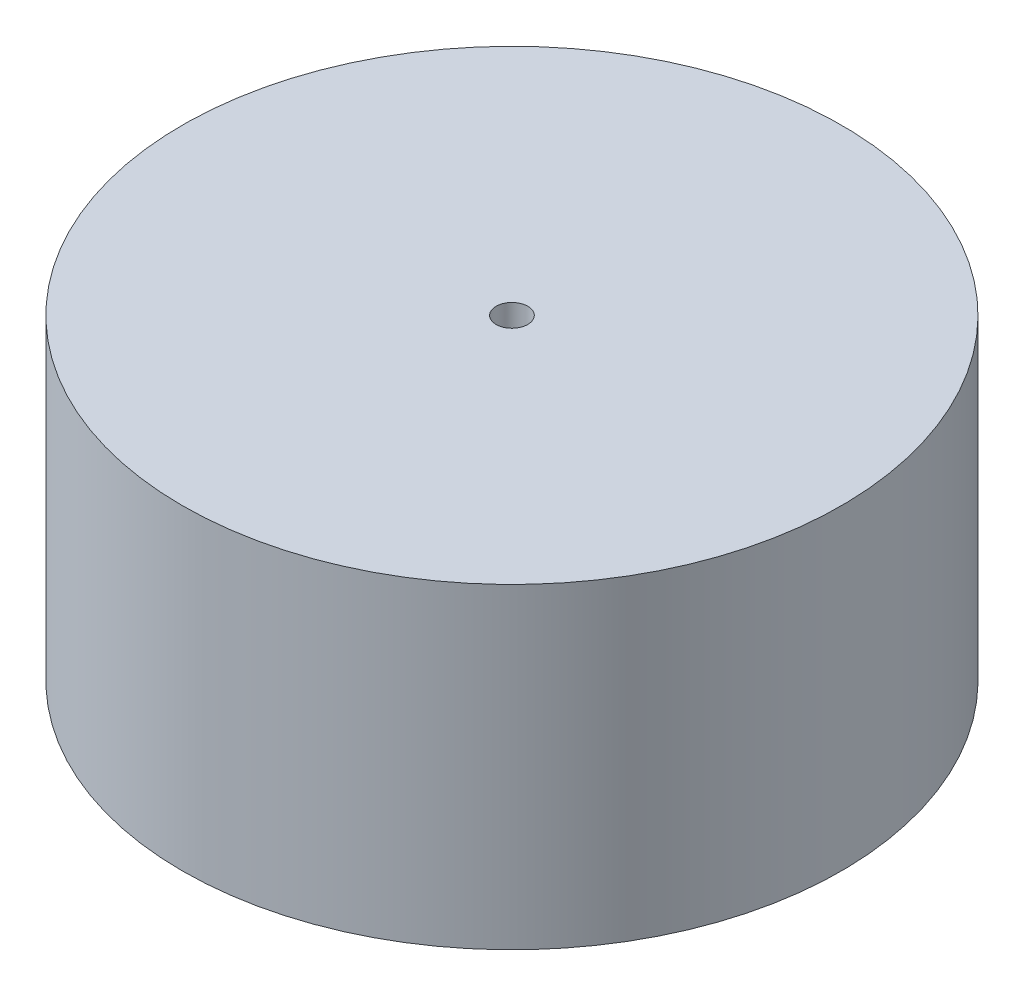
SolidWorks part; units mm, degrees
ref_plane "Front Plane" through (0, 0, 0) normal (0, 0, 1) x (1, 0, 0)
ref_plane "Top Plane" through (0, 0, 0) normal (0, 1, 0) x (1, 0, 0)
ref_plane "Right Plane" through (0, 0, 0) normal (1, 0, 0) x (0, 0, -1)
sketch "Sketch1" plane through (0, 0, 0) normal (0, 1, 0) x (1, 0, 0)
  circle A0 centre (0, 0) radius 62.5
  dimension "D1" = 125
extrude "Boss-Extrude1" add sketch "Sketch1" along normal blind 60
sketch "Sketch2" plane through (0, 0, 0) normal (0, -1, 0) x (1, 0, 0)
  circle A0 centre (0, 0) radius 3
extrude "Cut-Extrude1" cut sketch "Sketch2" against normal through all
